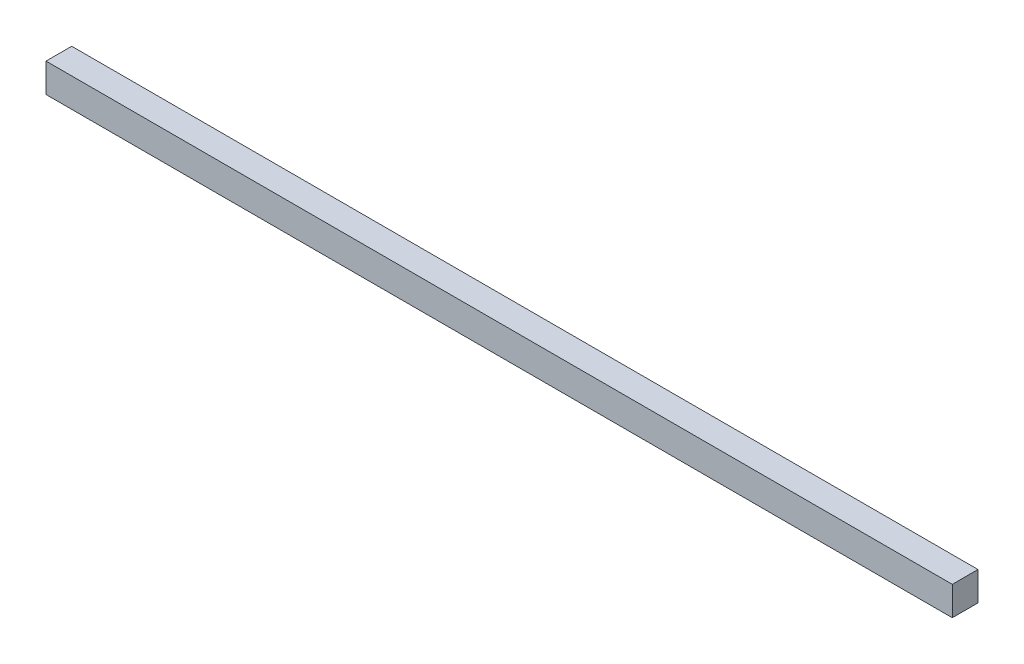
SolidWorks part; units mm, degrees
ref_plane "Спереди" through (0, 0, 0) normal (0, 0, 1) x (1, 0, 0)
ref_plane "Сверху" through (0, 0, 0) normal (0, 1, 0) x (1, 0, 0)
ref_plane "Справа" through (0, 0, 0) normal (1, 0, 0) x (0, 0, -1)
sketch "Эскиз1" plane through (0, 0, 0) normal (0, 0, 1) x (1, 0, 0)
  line L1 (-72.6423, 22.5317) -> (632.5465, 22.5317)
  line L2 (-72.6423, 22.5317) -> (-72.6423, 0)
  line L3 (-72.6423, 0) -> (632.5465, 0)
  line L4 (632.5465, 22.5317) -> (632.5465, 0)
extrude "Бобышка-Вытянуть1" add sketch "Эскиз1" along normal blind 20
